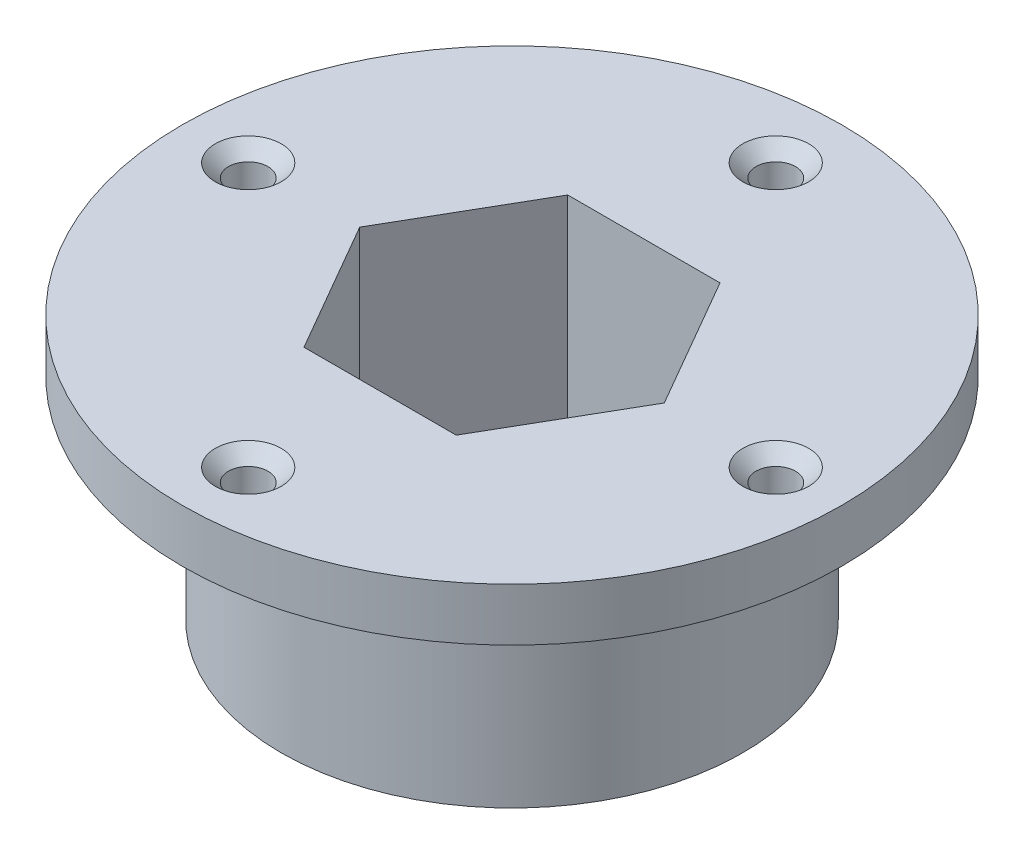
SolidWorks part; units mm, degrees
ref_plane "Front Plane" through (0, 0, 0) normal (0, 0, 1) x (1, 0, 0)
ref_plane "Top Plane" through (0, 0, 0) normal (0, 1, 0) x (1, 0, 0)
ref_plane "Right Plane" through (0, 0, 0) normal (1, 0, 0) x (0, 0, -1)
sketch "Sketch1" plane through (0, 0, 0) normal (0, 1, 0) x (1, 0, 0)
  line L1 (5.7735, -10) -> (11.547, 0)
  line L2 (11.547, 0) -> (5.7735, 10)
  line L3 (5.7735, 10) -> (-5.7735, 10)
  line L4 (-5.7735, 10) -> (-11.547, 0)
  line L5 (-11.547, 0) -> (-5.7735, -10)
  line L6 (-5.7735, -10) -> (5.7735, -10)
  circle A0 centre (0, 0) radius 17.5
  circle A1 centre (0, 0) radius 10 construction
  dimension "D1" = 35
  dimension "D2" = 20
extrude "Boss-Extrude1" add sketch "Sketch1" along normal blind 16
sketch "Sketch2" plane through (0, 16, 0) normal (0, 1, 0) x (1, 0, 0)
  circle A0 centre (0, 0) radius 12.5
  circle A1 centre (0, 0) radius 25
  dimension "D1" = 50
  dimension "D2" = 25
extrude "Boss-Extrude2" add sketch "Sketch2" along normal blind 4
sketch "Sketch3" plane through (0, 20, 0) normal (0, 1, 0) x (1, 0, 0)
  circle A0 centre (0, 20) radius 1.5
  circle A1 centre (20, 0) radius 1.5
  circle A2 centre (0, -20) radius 1.5
  circle A3 centre (-20, 0) radius 1.5
  point P12 (0, 0)
  dimension "D1" = 3
  dimension "D2" = 20
  dimension "D3" = 4
extrude "Cut-Extrude1" cut sketch "Sketch3" against normal through all
chamfer "Chamfer1" distance 1 angle 45 4 edges at (0, 20, -18.5) (20, 20, 1.5) (0, 20, 21.5) (-20, 20, 1.5)
sketch "Sketch4" plane through (0, 16, 0) normal (0, 1, 0) x (1, 0, 0)
  line L0 (-5.7735, 10) -> (-11.547, 0) construction
  line L1 (5.7735, 10) -> (-5.7735, 10) construction
  line L2 (11.547, 0) -> (5.7735, 10) construction
  line L3 (5.7735, -10) -> (11.547, 0) construction
  line L4 (-11.547, 0) -> (-5.7735, -10) construction
  line L5 (-5.7735, -10) -> (5.7735, -10) construction
  line L6 (-5.7735, -10) -> (5.7735, -10)
  line L7 (-11.547, 0) -> (-5.7735, -10)
  line L8 (5.7735, -10) -> (11.547, 0)
  line L9 (11.547, 0) -> (5.7735, 10)
  line L10 (5.7735, 10) -> (-5.7735, 10)
  line L11 (-5.7735, 10) -> (-11.547, 0)
  circle A1 centre (0, 0) radius 12.5
  circle A2 centre (0, 0) radius 12.5
  dimension "D1" = 0
extrude "Boss-Extrude3" add sketch "Sketch4" along normal up to surface (4 mm away) up to face at (0, 20, -17.5)
